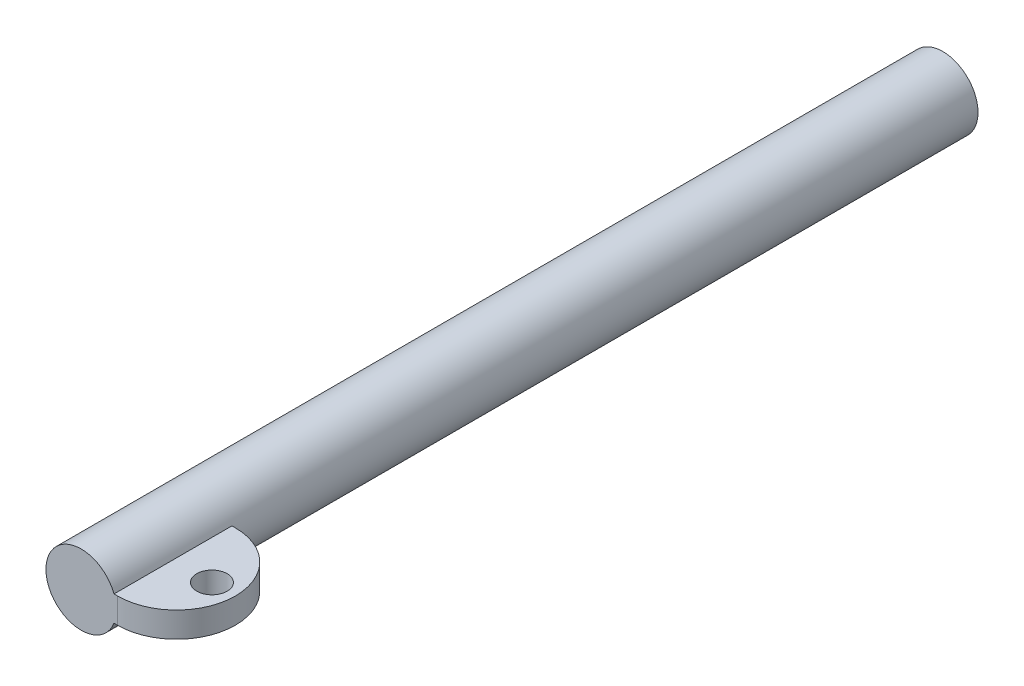
SolidWorks part; units mm, degrees
ref_plane "Front" through (0, 0, 0) normal (0, 0, 1) x (1, 0, 0)
ref_plane "Top" through (0, 0, 0) normal (0, 1, 0) x (1, 0, 0)
ref_plane "Right" through (0, 0, 0) normal (1, 0, 0) x (0, 0, -1)
sketch "Sketch1" plane through (0, 0, 0) normal (0, 0, 1) x (1, 0, 0)
  circle A0 centre (0, 0) radius 17.653
  point P3 (-17.653, 0)
  dimension "D1" = 35.306
extrude "Base-Extrude" add sketch "Sketch1" against normal blind 431.8
ref_plane "Plane2" through (0, 0, 0) normal (0, 1, 0) x (-1, 0, 0)
sketch "Sketch4" plane through (0, 0, 0) normal (0, 1, 0) x (-1, 0, 0)
  line L0 (-9.2566, -59.0746) -> (-9.2566, 0)
  line L1 (-18.2312, -59.0746) -> (-18.2312, 0) construction
  line L2 (-18.2312, -59.0746) -> (-9.2566, -59.0746)
  line L3 (-18.2312, 0) -> (-9.2566, 0)
  arc A0 (-18.2312, 0) -> (-18.2312, -59.0746) centre (-18.2312, -29.5373) ccw
  circle A1 centre (-36.0112, -29.5373) radius 7.62
  dimension "D1" = 17.78
  dimension "D2" = 29.5373
  dimension "D3" = 15.24
  dimension "D4" = 36.0112
  dimension "D5" = 8.9746
extrude "Boss-Extrude1" add sketch "Sketch4" along normal blind 6.35 and the other way blind 6.35
